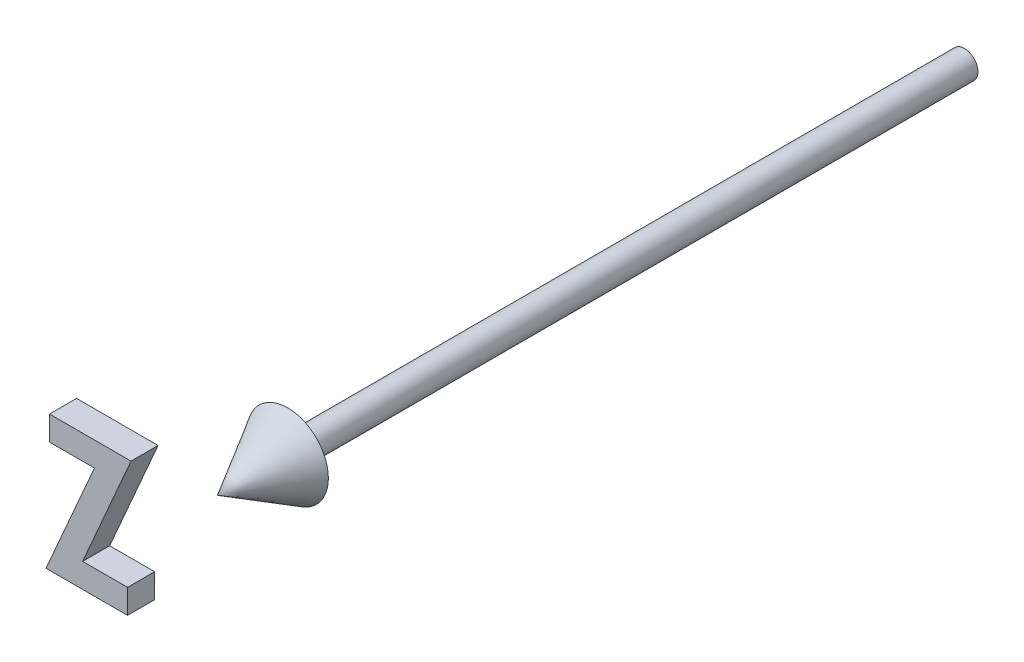
SolidWorks part; units mm, degrees
ref_plane "Front Plane" through (0, 0, 0) normal (0, 0, 1) x (1, 0, 0)
ref_plane "Top Plane" through (0, 0, 0) normal (0, 1, 0) x (1, 0, 0)
ref_plane "Right Plane" through (0, 0, 0) normal (1, 0, 0) x (0, 0, -1)
sketch "Sketch1" plane through (0, 0, 0) normal (0, 0, 1) x (1, 0, 0)
  circle A0 centre (0, 0) radius 1
  dimension "D1" = 2
extrude "Boss-Extrude1" add sketch "Sketch1" along normal blind 50
sketch "Sketch2" plane through (0, 0, 0) normal (0, 1, 0) x (1, 0, 0)
  line L0 (0, -50) -> (-3, -50)
  line L1 (-1, -50) -> (1, -50) construction
  line L2 (-3, -50) -> (0, -55.1962)
  line L3 (0, -55.1962) -> (0, -50)
  dimension "D1" = 3
  dimension "D2" = 60
revolve "Revolve1" add sketch "Sketch2" angle 360 about L3
ref_plane "Plane1" through (0, 0, 55.1962) normal (0, 0, 1) x (1, 0, 0)
sketch "Sketch4" plane through (0, 0, 55.1962) normal (0, 0, 1) x (1, 0, 0)
  line L0 (0, 0) -> (0, -5.0929) construction
  line L1 (-5, 0) -> (-9.8709, 0) construction
  text T0 "<b>Z</b>" font "Century Gothic" height 10
  dimension "D1" = 5
extrude "Boss-Extrude2" add sketch "Sketch4" along normal mid plane 2 separate body
